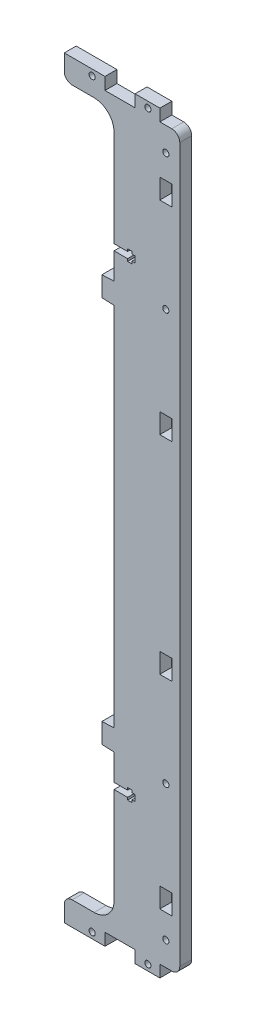
SolidWorks part; units mm, degrees
ref_plane "Front" through (0, 0, 0) normal (0, 0, 1) x (1, 0, 0)
ref_plane "Top" through (0, 0, 0) normal (0, 1, 0) x (1, 0, 0)
ref_plane "Right" through (0, 0, 0) normal (1, 0, 0) x (0, 0, -1)
sketch "Эскиз1" plane through (0, 0, 0) normal (0, 0, 1) x (1, 0, 0)
  line L0 (25.05, 159.1) -> (18.95, 159.1)
  line L1 (18.95, 159.1) -> (18.95, 149.1)
  line L2 (18.95, 149.1) -> (25.05, 149.1)
  line L3 (25.05, 149.1) -> (25.05, 159.1)
  line L4 (25.05, 57.1) -> (18.95, 57.1)
  line L5 (18.95, 57.1) -> (18.95, 47.1)
  line L6 (18.95, 47.1) -> (25.05, 47.1)
  line L7 (25.05, 47.1) -> (25.05, 57.1)
  line L8 (2.8, 115.55) -> (2.8, 114.35)
  line L9 (2.8, 114.35) -> (5, 114.35)
  line L10 (5, 114.35) -> (5, 115.55)
  line L11 (5, 115.55) -> (6.5, 115.55)
  line L12 (6.5, 115.55) -> (6.5, 118.65)
  line L13 (6.5, 118.65) -> (5, 118.65)
  line L14 (5, 118.65) -> (5, 119.85)
  line L15 (5, 119.85) -> (2.8, 119.85)
  line L16 (2.8, 119.85) -> (2.8, 118.65)
  line L17 (2.8, 118.65) -> (-4, 118.65)
  line L18 (-4, 167.1) -> (-4, 118.65)
  line L19 (-29, 189.1) -> (-29, 181.1)
  line L20 (-8.55, 189.1) -> (-29, 189.1)
  line L21 (-8.55, 189.1) -> (-8.55, 183)
  line L22 (-8.55, 183) -> (6.55, 183)
  line L23 (6.55, 183) -> (6.55, 189.1)
  line L24 (19, 183.1) -> (19, 189.1)
  line L25 (25, 183.1) -> (19, 183.1)
  line L26 (-10.1, 92.1) -> (-4, 91.85)
  line L27 (-10.1, 102.1) -> (-10.1, 92.1)
  line L28 (-4, 102.35) -> (-10.1, 102.1)
  line L29 (-4, 115.55) -> (2.8, 115.55)
  line L30 (19, 189.1) -> (6.55, 189.1)
  line L31 (-4, 115.55) -> (-4, 102.35)
  line L32 (-25, 177.1) -> (-14, 177.1)
  line L33 (25.05, -159.1) -> (18.95, -159.1)
  line L34 (18.95, -159.1) -> (18.95, -149.1)
  line L35 (18.95, -149.1) -> (25.05, -149.1)
  line L36 (25.05, -149.1) -> (25.05, -159.1)
  line L37 (25.05, -57.1) -> (18.95, -57.1)
  line L38 (18.95, -57.1) -> (18.95, -47.1)
  line L39 (18.95, -47.1) -> (25.05, -47.1)
  line L40 (25.05, -47.1) -> (25.05, -57.1)
  line L41 (2.8, -115.55) -> (2.8, -114.35)
  line L42 (2.8, -114.35) -> (5, -114.35)
  line L43 (5, -114.35) -> (5, -115.55)
  line L44 (5, -115.55) -> (6.5, -115.55)
  line L45 (6.5, -115.55) -> (6.5, -118.65)
  line L46 (6.5, -118.65) -> (5, -118.65)
  line L47 (5, -118.65) -> (5, -119.85)
  line L48 (5, -119.85) -> (2.8, -119.85)
  line L49 (2.8, -119.85) -> (2.8, -118.65)
  line L50 (2.8, -118.65) -> (-4, -118.65)
  line L51 (-4, -167.1) -> (-4, -118.65)
  line L52 (-29, -189.1) -> (-29, -181.1)
  line L53 (-8.55, -189.1) -> (-29, -189.1)
  line L54 (-8.55, -189.1) -> (-8.55, -183)
  line L55 (-8.55, -183) -> (6.55, -183)
  line L56 (6.55, -183) -> (6.55, -189.1)
  line L57 (19, -183.1) -> (19, -189.1)
  line L58 (25, -183.1) -> (19, -183.1)
  line L59 (-10.1, -92.1) -> (-4, -91.85)
  line L60 (-10.1, -102.1) -> (-10.1, -92.1)
  line L61 (-4, -102.35) -> (-10.1, -102.1)
  line L62 (-4, -115.55) -> (2.8, -115.55)
  line L63 (19, -189.1) -> (6.55, -189.1)
  line L64 (-4, -115.55) -> (-4, -102.35)
  line L65 (-25, -177.1) -> (-14, -177.1)
  line L66 (-4, -91.85) -> (-4, 91.85)
  line L67 (29, -179.1) -> (29, 179.1)
  circle A0 centre (-15, 186.1) radius 1.55
  circle A1 centre (13, 186.1) radius 1.55
  circle A2 centre (22, 103.1) radius 1.55
  circle A3 centre (22, 171.1) radius 1.55
  arc A4 (-4, 167.1) -> (-14, 177.1) centre (-14, 167.1) ccw
  arc A5 (-29, 181.1) -> (-25, 177.1) centre (-25, 181.1) ccw
  arc A6 (29, 179.1) -> (25, 183.1) centre (25, 179.1) ccw
  circle A7 centre (-15, -186.1) radius 1.55
  circle A8 centre (13, -186.1) radius 1.55
  circle A9 centre (22, -103.1) radius 1.55
  circle A10 centre (22, -171.1) radius 1.55
  arc A11 (-14, -177.1) -> (-4, -167.1) centre (-14, -167.1) ccw
  arc A12 (-25, -177.1) -> (-29, -181.1) centre (-25, -181.1) ccw
  arc A13 (25, -183.1) -> (29, -179.1) centre (25, -179.1) ccw
extrude "Бобышка-Вытянуть1" add sketch "Эскиз1" along normal blind 6
